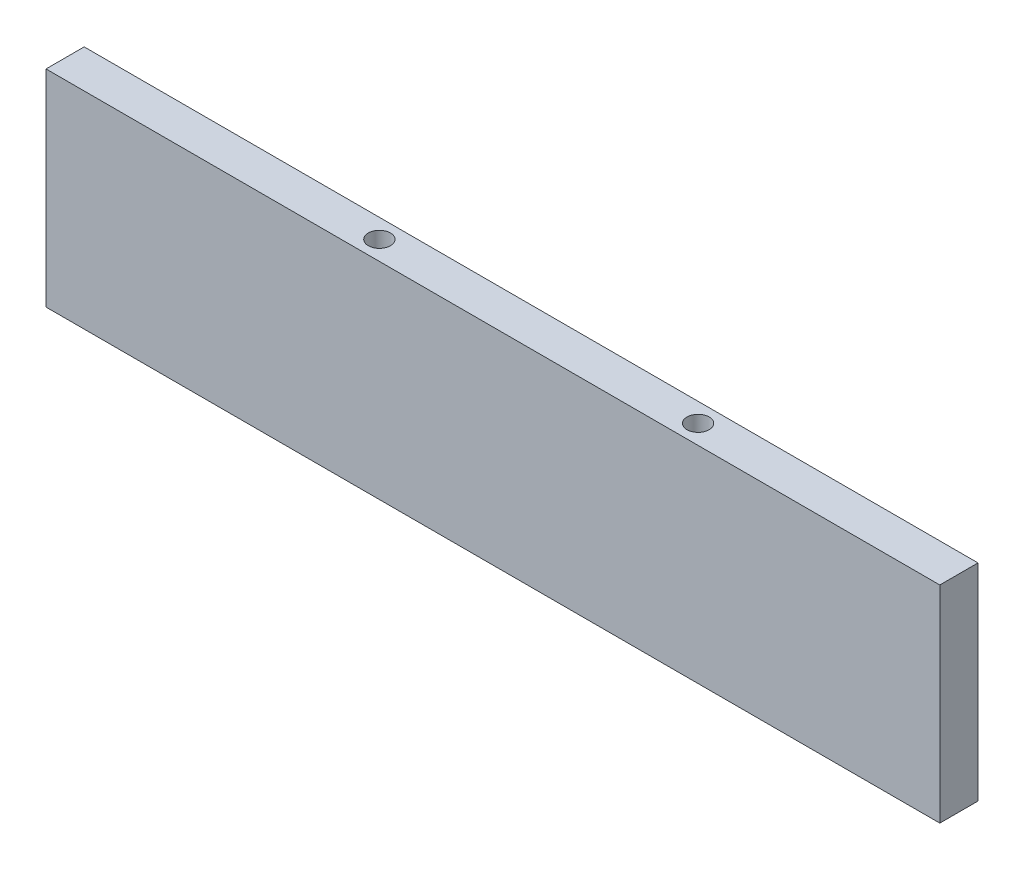
SolidWorks part; units mm, degrees
ref_plane "前视基准面" through (0, 0, 0) normal (0, 0, 1) x (1, 0, 0)
ref_plane "上视基准面" through (0, 0, 0) normal (0, 1, 0) x (1, 0, 0)
ref_plane "右视基准面" through (0, 0, 0) normal (1, 0, 0) x (0, 0, -1)
sketch "草图1" plane through (0, 0, 0) normal (0, 1, 0) x (1, 0, 0)
  line L1 (55, -2.5) -> (-62, -2.5)
  line L2 (55, -2.5) -> (55, 2.5)
  line L3 (55, 2.5) -> (-62, 2.5)
  line L4 (-62, -2.5) -> (-62, 2.5)
  point P0 (0, 0)
  dimension "D1" = 5
  dimension "D2" = 117
extrude "凸台-拉伸1" add sketch "草图1" along normal blind 27
sketch "草图2" plane through (0, 0, 0) normal (0, 1, 0) x (1, 0, 0)
  line L0 (0, -1000) -> (0, 49000) construction
  circle A0 centre (-20.86, 0) radius 1.45
  circle A1 centre (20.86, 0) radius 1.45
  dimension "D1" = 2.9
  dimension "D2" = 20.86
extrude "切除-拉伸1" cut sketch "草图2" along normal blind 30
